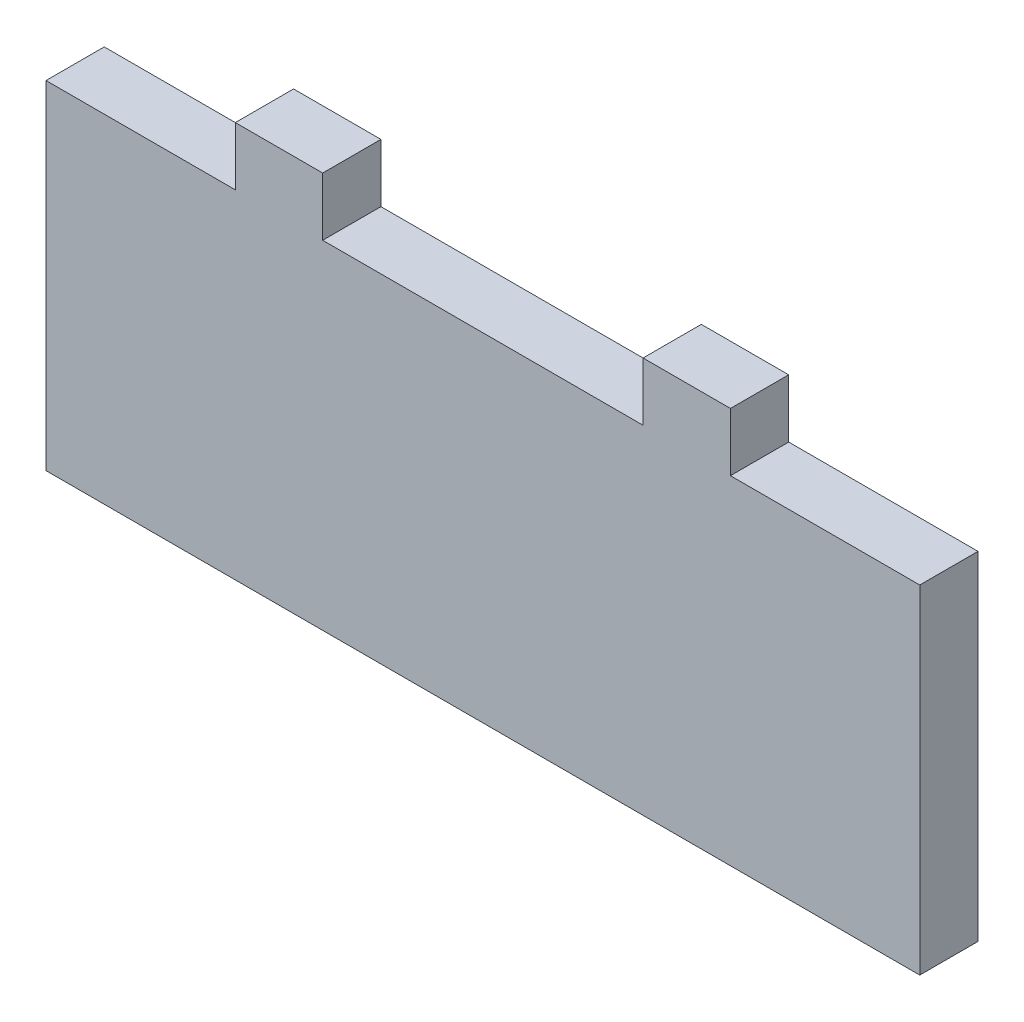
SolidWorks part; units mm, degrees
material "Acrylic (Medium-high impact)"
ref_plane "Front Plane" through (0, 0, 0) normal (0, 0, 1) x (1, 0, 0)
ref_plane "Top Plane" through (0, 0, 0) normal (0, 1, 0) x (1, 0, 0)
ref_plane "Right Plane" through (0, 0, 0) normal (1, 0, 0) x (0, 0, -1)
sketch "Sketch1" plane through (0, 0, 0) normal (0, 0, 1) x (1, 0, 0)
  line L0 (-53.975, 215.9) -> (-53.975, 228.6) construction
  line L1 (-95.25, 215.9) -> (-53.975, 215.9)
  line L2 (-95.25, 215.9) -> (-95.25, 142.24)
  line L3 (-95.25, 142.24) -> (95.25, 142.24)
  line L4 (95.25, 215.9) -> (95.25, 142.24)
  line L5 (-34.925, 228.6) -> (-53.975, 228.6) construction
  line L6 (-34.925, 215.9) -> (-34.925, 228.6) construction
  line L7 (34.925, 215.9) -> (34.925, 228.6) construction
  line L8 (53.975, 228.6) -> (34.925, 228.6) construction
  line L9 (53.975, 215.9) -> (53.975, 228.6) construction
  line L10 (-53.975, 215.9) -> (-53.975, 228.6)
  line L11 (-34.925, 228.6) -> (-53.975, 228.6)
  line L12 (-34.925, 215.9) -> (-34.925, 228.6)
  line L13 (34.925, 215.9) -> (34.925, 228.6)
  line L14 (53.975, 228.6) -> (34.925, 228.6)
  line L15 (53.975, 215.9) -> (53.975, 228.6)
  line L16 (-34.925, 215.9) -> (34.925, 215.9)
  line L17 (53.975, 215.9) -> (95.25, 215.9)
extrude "Extrude1" add sketch "Sketch1" against normal blind 12.7
sketch "Sketch2" plane through (0, 0, 0) normal (0, 0, 1) x (1, 0, 0)
  line L0 (-95.25, 142.24) -> (95.25, 142.24) construction
  line L1 (-25.4, 182.88) -> (25.4, 182.88)
  line L2 (-25.4, 182.88) -> (-25.4, 142.24)
  line L3 (-25.4, 142.24) -> (25.4, 142.24)
  line L4 (25.4, 182.88) -> (25.4, 142.24)
  point P6 (0, 182.88)
  dimension "D1" = 50.8
  dimension "D2" = 40.64
extrude "Cut-Extrude1" [suppressed] cut sketch "Sketch2" against normal through all
fillet "Fillet1" [suppressed] radius 6.4262
